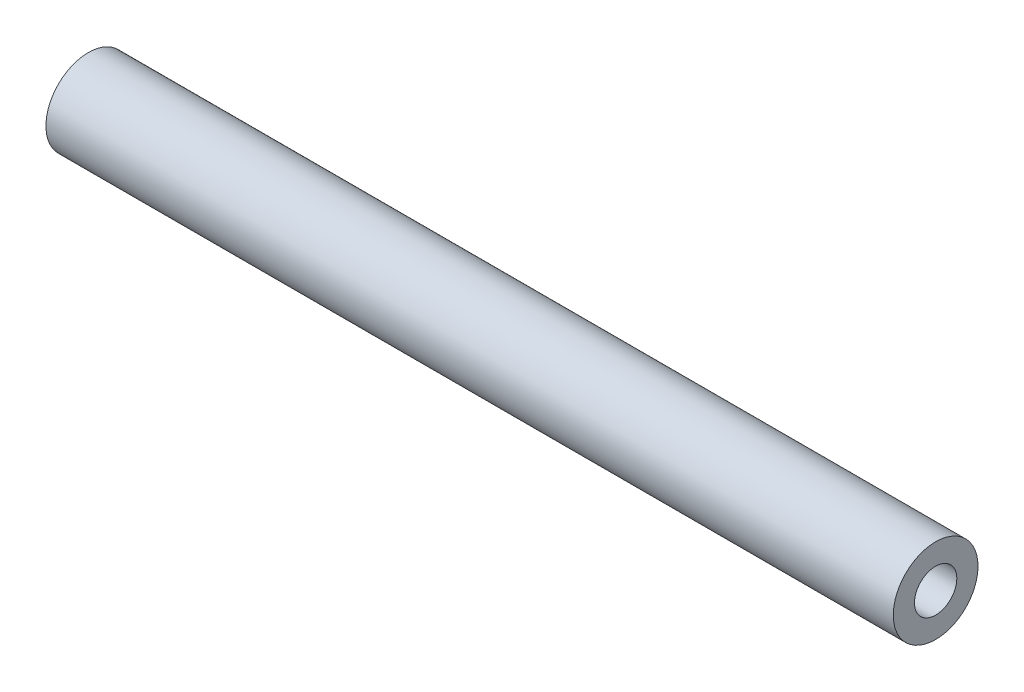
SolidWorks part; units mm, degrees
material "Pine"
ref_plane "Front Plane" through (0, 0, 0) normal (0, 0, 1) x (1, 0, 0)
ref_plane "Top Plane" through (0, 0, 0) normal (0, 1, 0) x (1, 0, 0)
ref_plane "Right Plane" through (0, 0, 0) normal (1, 0, 0) x (0, 0, -1)
sketch "Sketch1" plane through (0, 0, 0) normal (1, 0, 0) x (0, 0, -1)
  circle A0 centre (0, 0) radius 6.35
  dimension "D1" = 12.7
extrude "Boss-Extrude1" add sketch "Sketch1" along normal mid plane 127 contours A0
sketch "Sketch2" plane through (63.5, 0, 0) normal (1, 0, 0) x (0, 0, -1)
  circle A0 centre (0, 0) radius 3.175
  dimension "D1" = 6.35
extrude "Cut-Extrude1" cut sketch "Sketch2" along direction (1, 0, 0) on the side against the normal through all contours A0
scale "Scale1" scale about centroid uniform scaling yes scale factor 0.5
